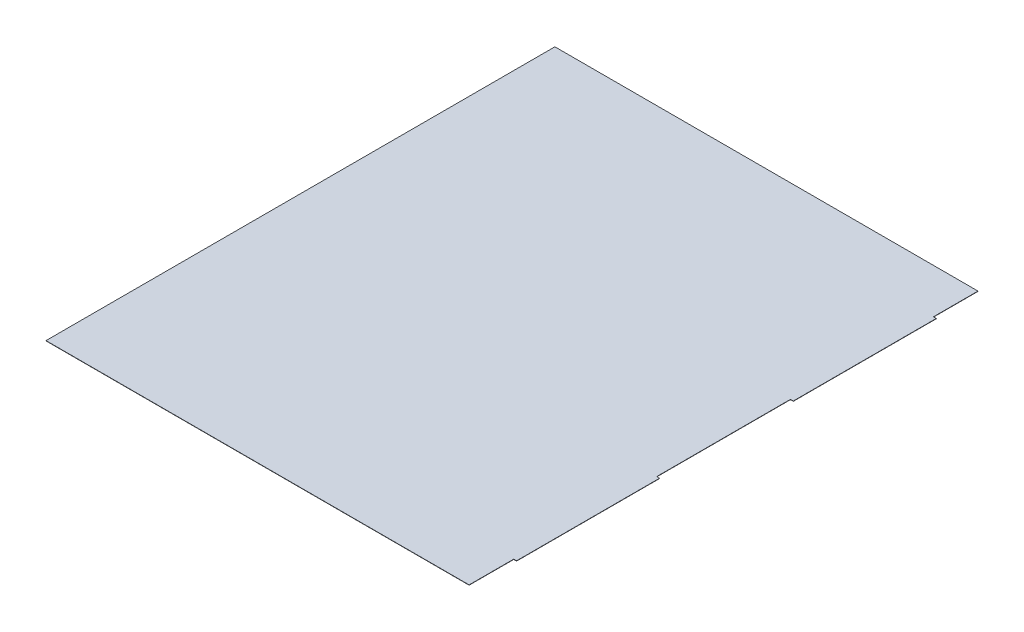
SolidWorks part; units mm, degrees
ref_plane "Front Plane" through (0, 0, 0) normal (0, 0, 1) x (1, 0, 0)
ref_plane "Top Plane" through (0, 0, 0) normal (0, 1, 0) x (1, 0, 0)
ref_plane "Right Plane" through (0, 0, 0) normal (1, 0, 0) x (0, 0, -1)
sketch "Sketch1" plane through (0, 0, 0) normal (0, 1, 0) x (1, 0, 0)
  line L1 (3700, -4450) -> (-3700, -4450)
  line L2 (3700, -4450) -> (3700, 4450)
  line L3 (3700, 4450) -> (3300, 4450)
  line L4 (-3700, -4450) -> (-3700, 4450)
  line L5 (3700, -4450) -> (-3700, 4450) construction
  line L6 (3700, 4450) -> (-3700, -4450) construction
  line L9 (2200, 4450) -> (-3700, 4450)
  line L10 (2159.1707, 4450) -> (3259.8921, 4450)
  line L11 (2200, 4450) -> (3300, 4450)
  point P0 (0, 0)
  dimension "D1" = 7400
  dimension "D2" = 8900
  dimension "D4" = 5900
extrude "Boss-Extrude1" add sketch "Sketch1" along normal blind 5 contours L11 L10 L9 L4 L1 L2 L3
sketch "Sketch2" plane through (0, 5, 0) normal (0, 1, 0) x (1, 0, 0)
  line L0 (3700, -4450) -> (3700, 4450) construction
  line L1 (3700, -3670) -> (3750, -3670)
  line L3 (3700, -1170) -> (3750, -1170)
  line L4 (3750, -3670) -> (3750, -1170)
  line L5 (-3700, 4450) -> (3700, 4450) construction
  line L6 (3700, 3670) -> (3750, 3670)
  line L7 (3700, -4450) -> (-3700, -4450) construction
  line L8 (3700, 3670) -> (3700, 1170)
  line L9 (3700, 1170) -> (3750, 1170)
  line L10 (3750, 3670) -> (3750, 1170)
  line L11 (3700, 3670) -> (3750, 1170) construction
  line L12 (3700, 1170) -> (3750, 3670) construction
  point P4 (3725, -2995)
  point P13 (3725, 2420)
  line M9 (3700, -4450) -> (3700, 4450)
  dimension "D1" = 780
  dimension "D2" = 2500
  dimension "D3" = 50
  dimension "D4" = 780
  dimension "D5" = 50
  dimension "D6" = 2500
extrude "Boss-Extrude2" add sketch "Sketch2" against normal blind 5 contours L1 L4 L3 M9 | L10 L9 L8 L6
